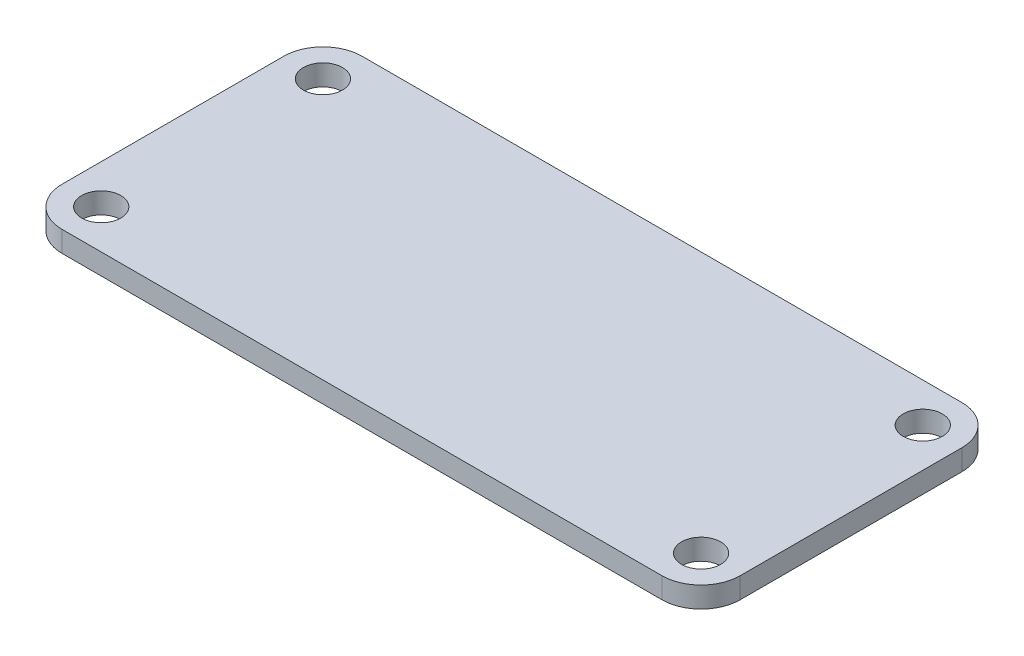
SolidWorks part; units mm, degrees
ref_plane "前视基准面" through (0, 0, 0) normal (0, 0, 1) x (1, 0, 0)
ref_plane "上视基准面" through (0, 0, 0) normal (0, 1, 0) x (1, 0, 0)
ref_plane "右视基准面" through (0, 0, 0) normal (1, 0, 0) x (0, 0, -1)
sketch "Sketch2" plane through (0, 0, 0) normal (0, 1, 0) x (1, 0, 0)
  line L1 (-26, 11.5) -> (26, 11.5)
  line L2 (-26, 11.5) -> (-26, -11.5)
  line L3 (-26, -11.5) -> (26, -11.5)
  line L4 (26, 11.5) -> (26, -11.5)
  line L5 (-26, 11.5) -> (26, -11.5) construction
  line L6 (-26, -11.5) -> (26, 11.5) construction
  point P0 (0, 0)
  dimension "D1" = 52
  dimension "D2" = 23
extrude "Boss-Extrude1" add sketch "Sketch2" along normal blind 1.6
fillet "Fillet1" radius 3 4 edges at (-26, 0.8, -11.5) (-26, 0.8, 11.5) (26, 0.8, -11.5) (26, 0.8, 11.5)
sketch "Sketch5" plane through (0, 1.6, 0) normal (0, 1, 0) x (1, 0, 0)
  line L0 (0, 0) -> (0, 11.5) construction
  line L1 (23, 11.5) -> (-23, 11.5) construction
  line L2 (0, 0) -> (5.0318, 0) construction
  circle A0 centre (-23, 8.5) radius 1.5
  circle A1 centre (23, 8.5) radius 1.5
  circle A2 centre (23, -8.5) radius 1.5
  circle A3 centre (-23, -8.5) radius 1.5
sketch "Sketch6" plane through (0, 1.6, 0) normal (0, 1, 0) x (1, 0, 0)
extrude "Cut-Extrude1" cut sketch "Sketch5" against normal blind 10
